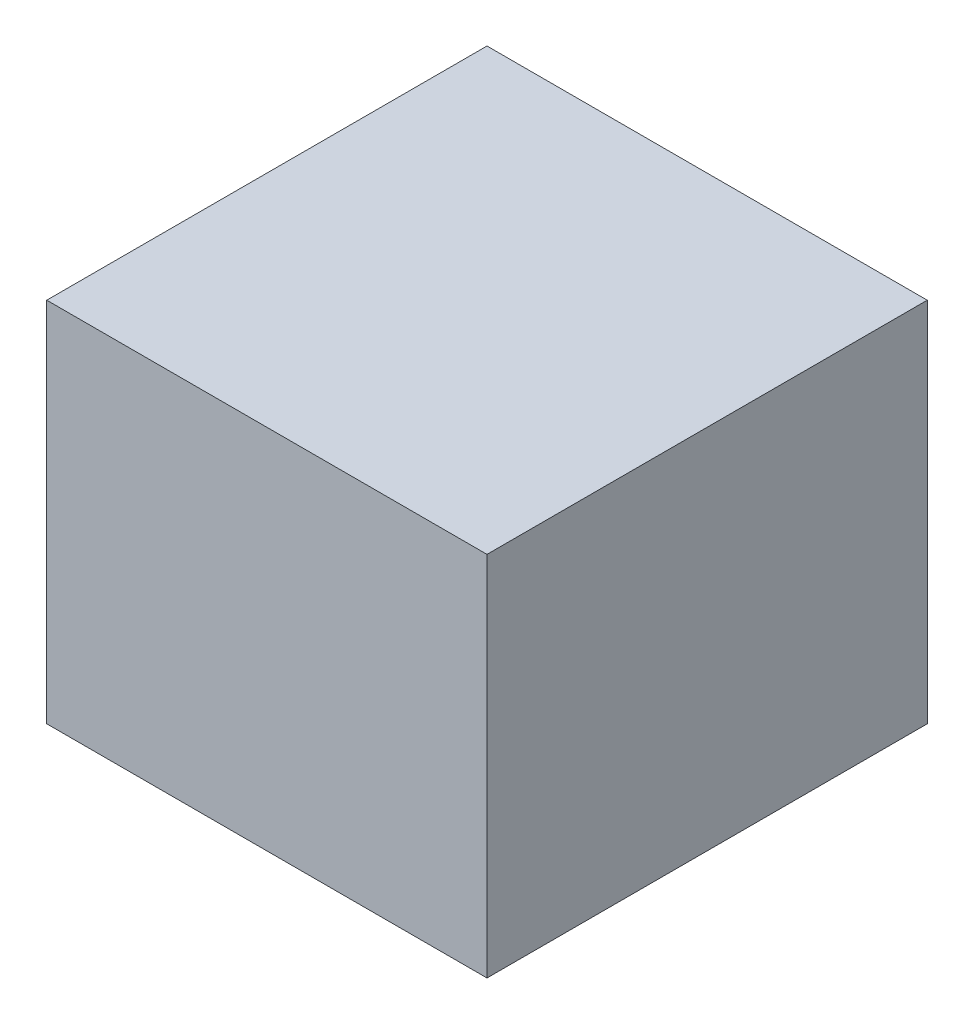
SolidWorks part; units mm, degrees
material "Cast Alloy Steel"
ref_plane "Front Plane" through (0, 0, 0) normal (0, 0, 1) x (1, 0, 0)
ref_plane "Top Plane" through (0, 0, 0) normal (0, 1, 0) x (1, 0, 0)
ref_plane "Right Plane" through (0, 0, 0) normal (1, 0, 0) x (0, 0, -1)
sketch "Sketch1" plane through (0, 0, 0) normal (0, 1, 0) x (1, 0, 0)
  line L0 (-6, 6) -> (6, -6) construction
  line L1 (-6, 6) -> (6, 6)
  line L2 (-6, 6) -> (-6, -6)
  line L3 (-6, -6) -> (6, -6)
  line L4 (6, 6) -> (6, -6)
  point P4 (0, 0)
  dimension "D1" = 12
  dimension "D2" = 12
extrude "Boss-Extrude1" add sketch "Sketch1" along normal blind 10
sketch "Sketch2" plane through (0, 0, 0) normal (0, -1, 0) x (1, 0, 0)
  circle A0 centre (0, 0) radius 3
  dimension "D1" = 6
extrude "Cut-Extrude1" cut sketch "Sketch2" against normal blind 5
